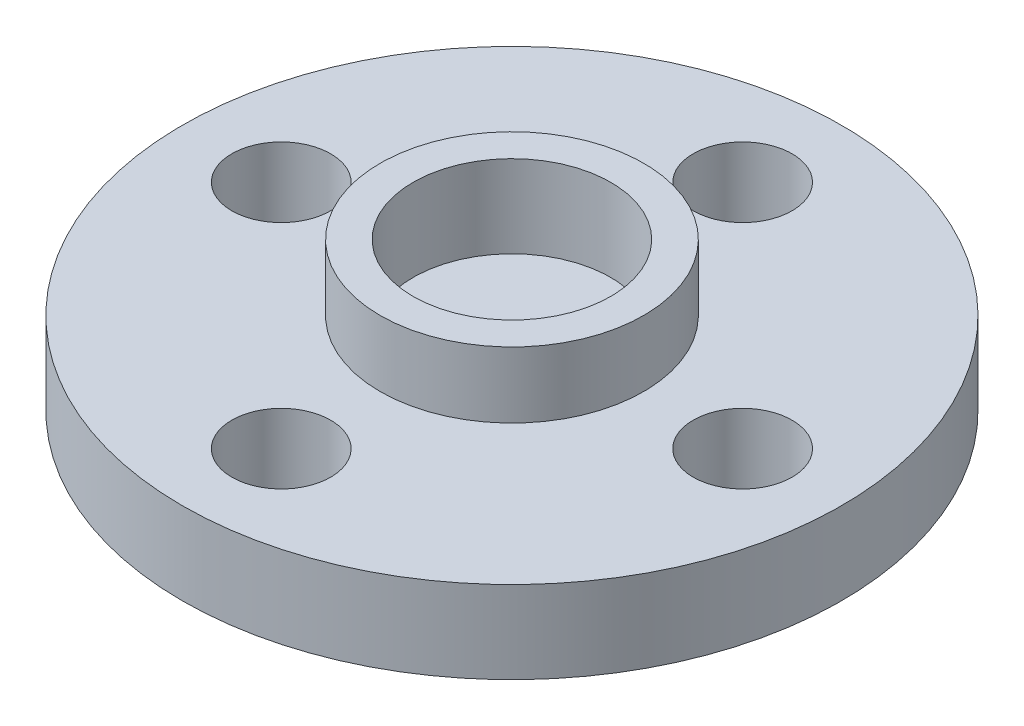
SolidWorks part; units mm, degrees
ref_plane "Front Plane" through (0, 0, 0) normal (0, 0, 1) x (1, 0, 0)
ref_plane "Top Plane" through (0, 0, 0) normal (0, 1, 0) x (1, 0, 0)
ref_plane "Right Plane" through (0, 0, 0) normal (1, 0, 0) x (0, 0, -1)
sketch "Sketch1" plane through (0, 0, 0) normal (0, 1, 0) x (1, 0, 0)
  circle A0 centre (0, 0) radius 10
  dimension "D1" = 20
extrude "Boss-Extrude1" add sketch "Sketch1" along normal blind 2.5
sketch "Sketch2" plane through (0, 2.5, 0) normal (0, 1, 0) x (1, 0, 0)
  circle A0 centre (0, 0) radius 3
  circle A1 centre (0, 0) radius 4
  dimension "D1" = 8
  dimension "D2" = 6
extrude "Boss-Extrude2" add sketch "Sketch2" along normal blind 2
sketch "Sketch3" plane through (0, 2.5, 0) normal (0, 1, 0) x (1, 0, 0)
  circle A0 centre (0, 0) radius 3
extrude "Cut-Extrude1" cut sketch "Sketch3" against normal blind 0.5
sketch "Sketch4" plane through (0, 2, 0) normal (0, 1, 0) x (1, 0, 0)
  line L0 (0, 0) -> (0, 7) construction
  circle A0 centre (0, 7) radius 1.5
  circle A1 centre (7, 0) radius 1.5
  circle A2 centre (0, -7) radius 1.5
  circle A3 centre (-7, 0) radius 1.5
  point P13 (0, 0)
  dimension "D2" = 3
  dimension "D1" = 7
  dimension "D3" = 4
extrude "Cut-Extrude3" cut sketch "Sketch4" against normal up to next and the other way through all contours A0 | A1 | A2 | A3
